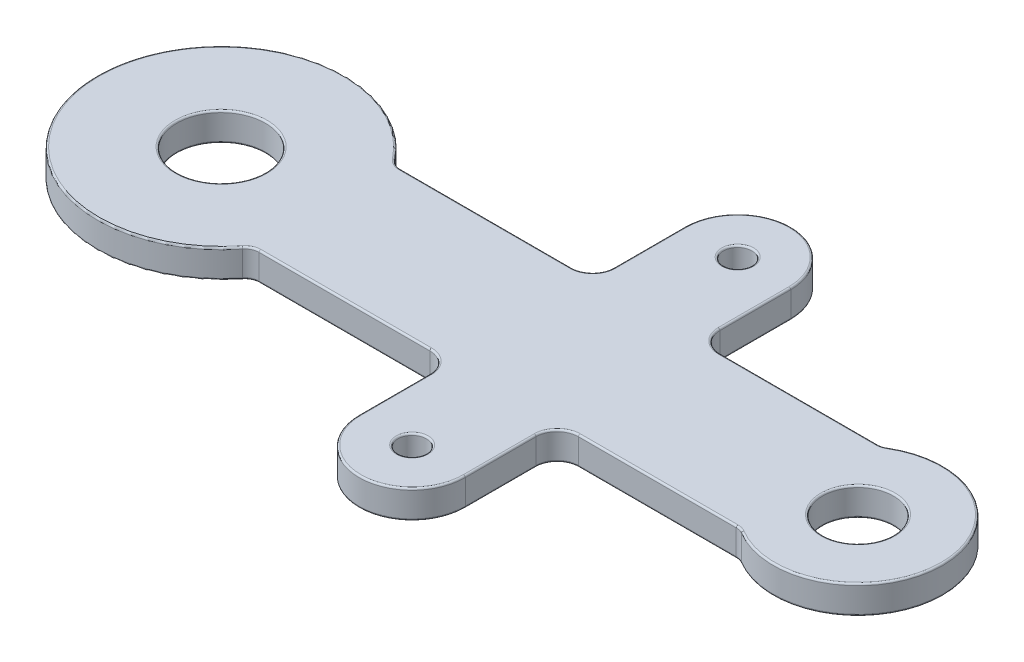
SolidWorks part; units mm, degrees
ref_plane "前视基准面" through (0, 0, 0) normal (0, 0, 1) x (1, 0, 0)
ref_plane "上视基准面" through (0, 0, 0) normal (0, 1, 0) x (1, 0, 0)
ref_plane "右视基准面" through (0, 0, 0) normal (1, 0, 0) x (0, 0, -1)
sketch "草图1" plane through (0, 0, 0) normal (0, 1, 0) x (1, 0, 0)
  line L0 (-79.8254, 0) -> (43.5663, 0) construction
  line L1 (0, 81.5805) -> (0, -29.6577) construction
  line L2 (28.7194, 20.0049) -> (85, 20.0049)
  line L3 (28.7194, -20.0049) -> (85, -20.0049)
  line L4 (115, 20.0049) -> (166.7409, 20.0049)
  line L5 (115, -20.0049) -> (166.7409, -20.0049)
  line L7 (85, 46) -> (85, 20.0049)
  line L8 (115, 46) -> (115, 20.0049)
  line L9 (115, -46) -> (115, -20.0049)
  line L10 (85, -46) -> (85, -20.0049)
  circle A0 centre (0, 0) radius 12.5
  arc A1 (28.7194, 20.0049) -> (28.7194, -20.0049) centre (0, 0) ccw
  circle A2 centre (100, 46) radius 4
  circle A3 centre (180, 0) radius 10
  arc A4 (166.7409, -20.0049) -> (166.7409, 20.0049) centre (180, 0) ccw
  circle A5 centre (100, -46) radius 4
  arc A8 (115, 46) -> (85, 46) centre (100, 46) ccw
  arc A9 (115, -46) -> (85, -46) centre (100, -46) cw
  point P9 (180, 0)
  point P13 (28.7194, 20.0049)
  point P24 (100, 0)
  point P29 (85, 46)
  point P30 (115, 46)
extrude "凸台-拉伸1" add sketch "草图1" along normal blind 8
fillet "圆角1" radius 6 1 edges at (85, 4, -20.0049)
fillet "圆角2" radius 6 1 edges at (115, 4, -20.0049)
fillet "圆角3" radius 6 1 edges at (115, 4, 20.0049)
fillet "圆角4" radius 6 1 edges at (85, 4, 20.0049)
fillet "圆角5" radius 4 1 edges at (28.7194, 4, -20.0049)
fillet "圆角6" radius 4 1 edges at (28.7194, 4, 20.0049)
fillet "圆角7" radius 4 1 edges at (166.7409, 4, 20.0049)
fillet "圆角8" radius 4 1 edges at (166.7409, 4, -20.0049)
fillet "圆角9" radius 0.5 48 edges at (180, 8, 10) (100, 8, -42) (0, 8, 12.5) (100, 8, 42) (204, 8, 0) (166.6543, 8, 20.1502) (143.293, 8, 20.0049) (116.7574, 8, 21.7622) (115, 8, 36.0024) (100, 8, 61) (85, 8, 36.0024) (83.2426, 8, 21.7622) (54.8685, 8, 20.0049) (28.9832, 8, 20.4099) (-35, 8, 0) (28.9832, 8, -20.4099) (54.8685, 8, -20.0049) (83.2426, 8, -21.7622) (85, 8, -36.0024) (100, 8, -61) (115, 8, -36.0024) (116.7574, 8, -21.7622) (143.293, 8, -20.0049) (166.6543, 8, -20.1502) (180, 0, 10) (100, 0, 42) (100, 0, -42) (0, 0, 12.5) (28.9832, 0, 20.4099) (54.8685, 0, 20.0049) (83.2426, 0, 21.7622) (85, 0, 36.0024) (100, 0, 61) (115, 0, 36.0024) (116.7574, 0, 21.7622) (143.293, 0, 20.0049) (166.6543, 0, 20.1502) (204, 0, 0) (166.6543, 0, -20.1502) (143.293, 0, -20.0049) (116.7574, 0, -21.7622) (115, 0, -36.0024) (100, 0, -61) (85, 0, -36.0024) (83.2426, 0, -21.7622) (54.8685, 0, -20.0049) (28.9832, 0, -20.4099) (-35, 0, 0)
